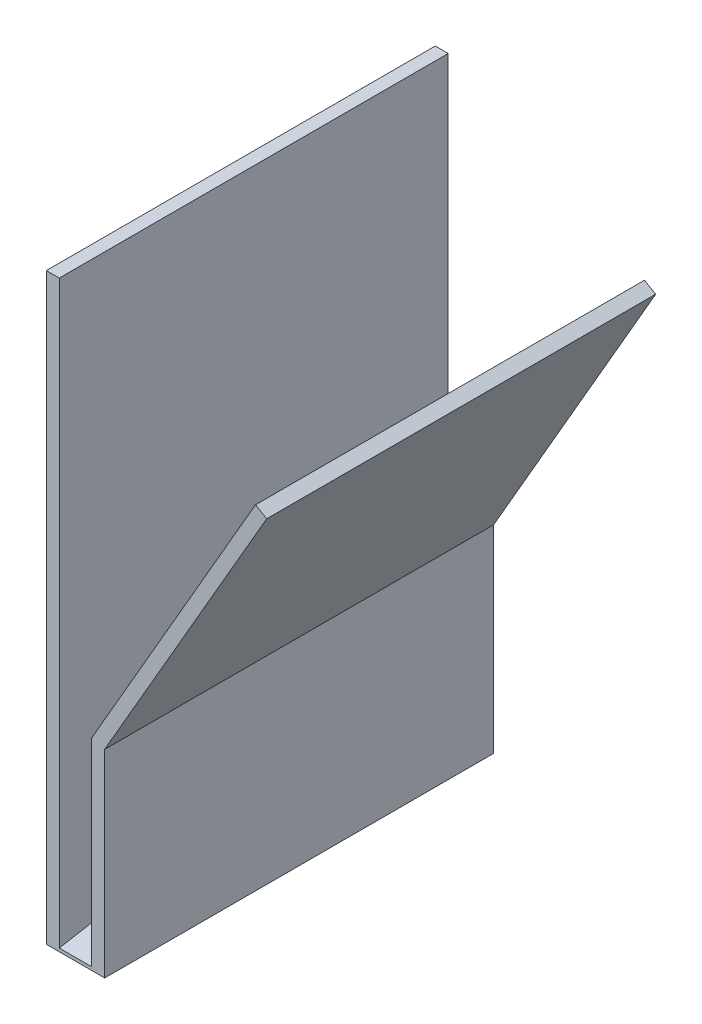
SolidWorks part; units mm, degrees
ref_plane "Front Plane" through (0, 0, 0) normal (0, 0, 1) x (1, 0, 0)
ref_plane "Top Plane" through (0, 0, 0) normal (0, 1, 0) x (1, 0, 0)
ref_plane "Right Plane" through (0, 0, 0) normal (1, 0, 0) x (0, 0, -1)
sketch "Sketch1" plane through (0, 0, 0) normal (0, 0, 1) x (1, 0, 0)
  line L1 (0, 0) -> (4, 0)
  line L2 (0, 0) -> (0, 180)
  line L3 (0, 180) -> (4, 180)
  line L4 (4, 0) -> (4, 180)
  dimension "D1" = 180
  dimension "D2" = 4
extrude "Boss-Extrude1" add sketch "Sketch1" along normal blind 120
sketch "Sketch2" plane through (4, 0, 0) normal (1, 0, 0) x (0, 0, -1)
  line L0 (-120, 0) -> (-120, 1)
  line L1 (-120, 0) -> (-120, 180) construction
  line L2 (-120, 1) -> (0, 22.1592)
  line L3 (0, 0) -> (0, 180) construction
  line L4 (0, 22.1592) -> (0, 0)
  line L5 (0, 0) -> (-120, 0)
  dimension "D1" = 1
  dimension "D2" = 10
extrude "Boss-Extrude2" add sketch "Sketch2" along normal blind 10
sketch "Sketch4" plane through (0, 0, 0) normal (0, 0, -1) x (-1, 0, 0)
  line L0 (-14, 0) -> (-14, 62.1592)
  line L1 (-14, 62.1592) -> (-64.5359, 149.69)
  line L2 (-64.5359, 149.69) -> (-68, 147.69)
  line L3 (-68, 147.69) -> (-18, 61.0874)
  line L4 (-18, 61.0874) -> (-18, 0)
  line L5 (-18, 0) -> (-14, 0)
  line L6 (-14, 22.1592) -> (-4, 22.1592) construction
  dimension "D1" = 4
  dimension "D2" = 40
  dimension "D3" = 4
  dimension "D4" = 100
  dimension "D5" = 30
extrude "Boss-Extrude3" add sketch "Sketch4" against normal up to surface (120 mm away) up to face at (6, 60.3333, 120)
